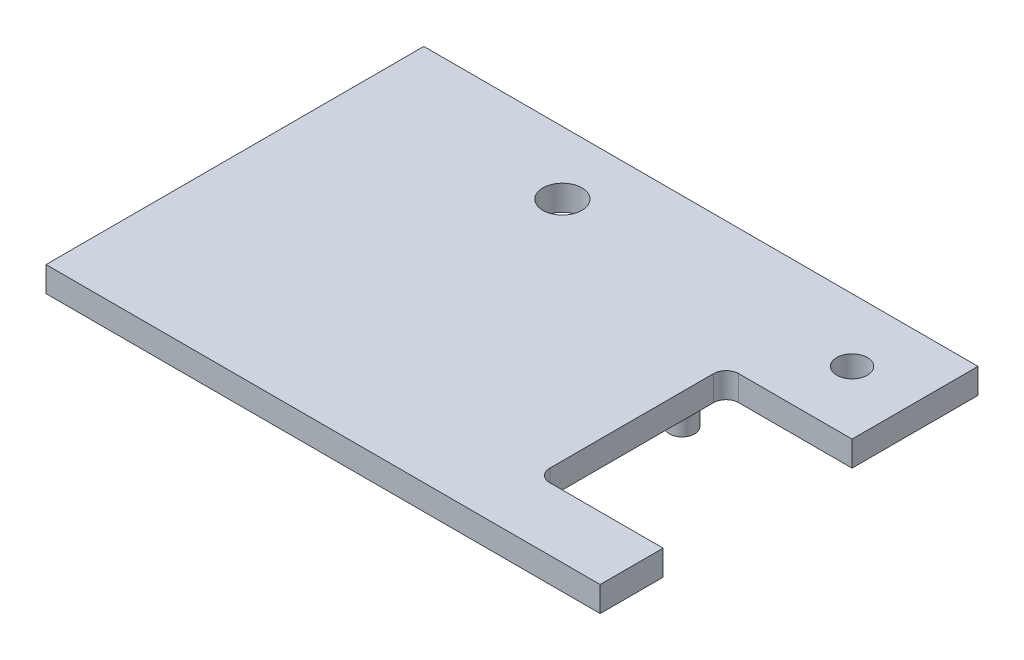
SolidWorks part; units mm, degrees
material "CA"
ref_plane "Front Plane" through (0, 0, 0) normal (0, 0, 1) x (1, 0, 0)
ref_plane "Top Plane" through (0, 0, 0) normal (0, 1, 0) x (1, 0, 0)
ref_plane "Right Plane" through (0, 0, 0) normal (1, 0, 0) x (0, 0, -1)
sketch "Sketch1" plane through (0, 0, 0) normal (0, 1, 0) x (1, 0, 0)
  line L1 (-22, -15) -> (22, -15)
  line L2 (-22, -15) -> (-22, 15)
  line L3 (-22, 15) -> (22, 15)
  line L4 (22, -15) -> (22, 15)
  line L5 (-22, -15) -> (22, 15) construction
  line L6 (-22, 15) -> (22, -15) construction
  circle A0 centre (17, 10) radius 1.2192
  circle A1 centre (-6, 10) radius 1.55
  point P0 (0, 0)
  dimension "D5" = 2.4384
  dimension "D8" = 3.1
  dimension "D1" = 30
  dimension "D2" = 44
  dimension "D3" = 5
  dimension "D4" = 5
  dimension "D6" = 5
  dimension "D7" = 16
extrude "Boss-Extrude1" add sketch "Sketch1" along normal blind 2
sketch "Sketch2" plane through (0, 0, 0) normal (0, -1, 0) x (-1, 0, 0)
  line L0 (-22, 15) -> (22, 15) construction
  line L1 (22, 15) -> (22, -15) construction
  line L2 (-22, -15) -> (-22, 15) construction
  line L3 (22, -15) -> (-22, -15) construction
  circle A0 centre (19, 12) radius 1
  circle A1 centre (-10, -12.5) radius 1
  dimension "D3" = 2
  dimension "D6" = 2
  dimension "D1" = 3
  dimension "D2" = 3
  dimension "D4" = 12
  dimension "D5" = 2.5
extrude "Boss-Extrude2" add sketch "Sketch2" along normal blind 1.5
fillet "Fillet1" radius 1 2 edges at (10, -1.5, 11.5) (-19, -1.5, -13)
sketch "Sketch4" plane through (0, 0, 0) normal (0, -1, 0) x (1, 0, 0)
  line L0 (-22, 15) -> (22, 15) construction
  line L1 (-19.5, -4.5) -> (-17.5, -4.5)
  line L2 (-19.5, -4.5) -> (-19.5, -2.5)
  line L3 (-19.5, -2.5) -> (-17.5, -2.5)
  line L4 (-17.5, -4.5) -> (-17.5, -2.5)
  line L5 (-19.5, -4.5) -> (-17.5, -2.5) construction
  line L6 (-19.5, -2.5) -> (-17.5, -4.5) construction
  line L7 (-22, -15) -> (-22, 15) construction
  line L8 (9, -4.5) -> (11, -4.5)
  line L9 (9, -4.5) -> (9, -2.5)
  line L10 (9, -2.5) -> (11, -2.5)
  line L11 (11, -4.5) -> (11, -2.5)
  line L12 (9, -4.5) -> (11, -2.5) construction
  line L13 (9, -2.5) -> (11, -4.5) construction
  line L14 (11, 7.5) -> (9, 7.5)
  line L15 (11, 7.5) -> (11, 9.5)
  line L16 (11, 9.5) -> (9, 9.5)
  line L17 (9, 7.5) -> (9, 9.5)
  line L18 (11, 7.5) -> (9, 9.5) construction
  line L19 (11, 9.5) -> (9, 7.5) construction
  circle A0 centre (10, -3.5) radius 1
  circle A1 centre (10, 8.5) radius 1
  circle A2 centre (-18.5, -3.5) radius 1
  point P0 (-18.5, -3.5)
  point P9 (10, -3.5)
  point P14 (10, 8.5)
  dimension "D1" = 19.5
  dimension "D2" = 2.5
  dimension "D3" = 2
  dimension "D4" = 2
  dimension "D5" = 19.5
  dimension "D6" = 33
  dimension "D7" = 2
  dimension "D8" = 33
  dimension "D9" = 5.5
  dimension "D10" = 2
  dimension "D11" = 2
extrude "Boss-Extrude3" add sketch "Sketch4" along normal blind 2.4 contours A1 | A2 | A0
sketch "Sketch5" plane through (0, 2, 0) normal (0, 1, 0) x (1, 0, 0)
  line L0 (22, -15) -> (22, 15) construction
  line L1 (22, 5) -> (12, 5)
  line L2 (22, 5) -> (22, -10)
  line L3 (22, -10) -> (12, -10)
  line L4 (12, 5) -> (12, -10)
  line L6 (-22, -15) -> (22, -15) construction
  dimension "D1" = 10
  dimension "D2" = 5
  dimension "D3" = 20
extrude "Cut-Extrude1" cut sketch "Sketch5" against normal through all
fillet "Fillet2" radius 1 2 edges at (12, 1, 10) (12, 1, -5)
